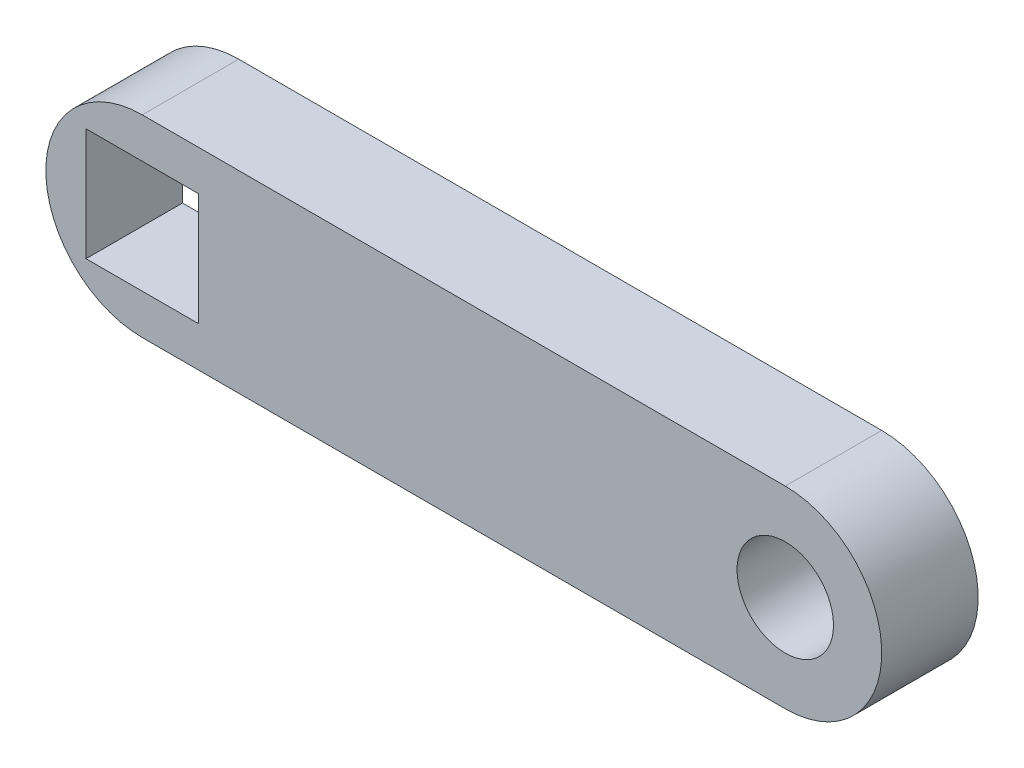
SolidWorks part; units mm, degrees
ref_plane "Plan de face" through (0, 0, 0) normal (0, 0, 1) x (1, 0, 0)
ref_plane "Plan de dessus" through (0, 0, 0) normal (0, 1, 0) x (1, 0, 0)
ref_plane "Plan de droite" through (0, 0, 0) normal (1, 0, 0) x (0, 0, -1)
sketch "Esquisse1" plane through (0, 0, 0) normal (0, 0, 1) x (1, 0, 0)
  line L0 (0, 3) -> (20, 3)
  line L3 (20, -3) -> (0, -3)
  line L5 (-1.75, 1.75) -> (1.75, 1.75)
  line L6 (-1.75, 1.75) -> (-1.75, -1.75)
  line L7 (-1.75, -1.75) -> (1.75, -1.75)
  line L8 (1.75, 1.75) -> (1.75, -1.75)
  line L9 (-1.75, 1.75) -> (1.75, -1.75) construction
  line L10 (-1.75, -1.75) -> (1.75, 1.75) construction
  arc A2 (0, 3) -> (0, -3) centre (0, 0) ccw
  arc A3 (20, 3) -> (20, -3) centre (20, 0) cw
  circle A5 centre (20, 0) radius 1.5
  circle A6 centre (0, 0) radius 1.75 construction
  point P2 (0, 0)
  point P14 (0, 0)
  point P15 (-1.7954, 1.8169)
  dimension "D2" = 3
  dimension "D3" = 3
  dimension "D5" = 3
  dimension "D6" = 3.5
  dimension "D4" = 20
extrude "Boss.-Extru.1" add sketch "Esquisse1" along normal blind 3
